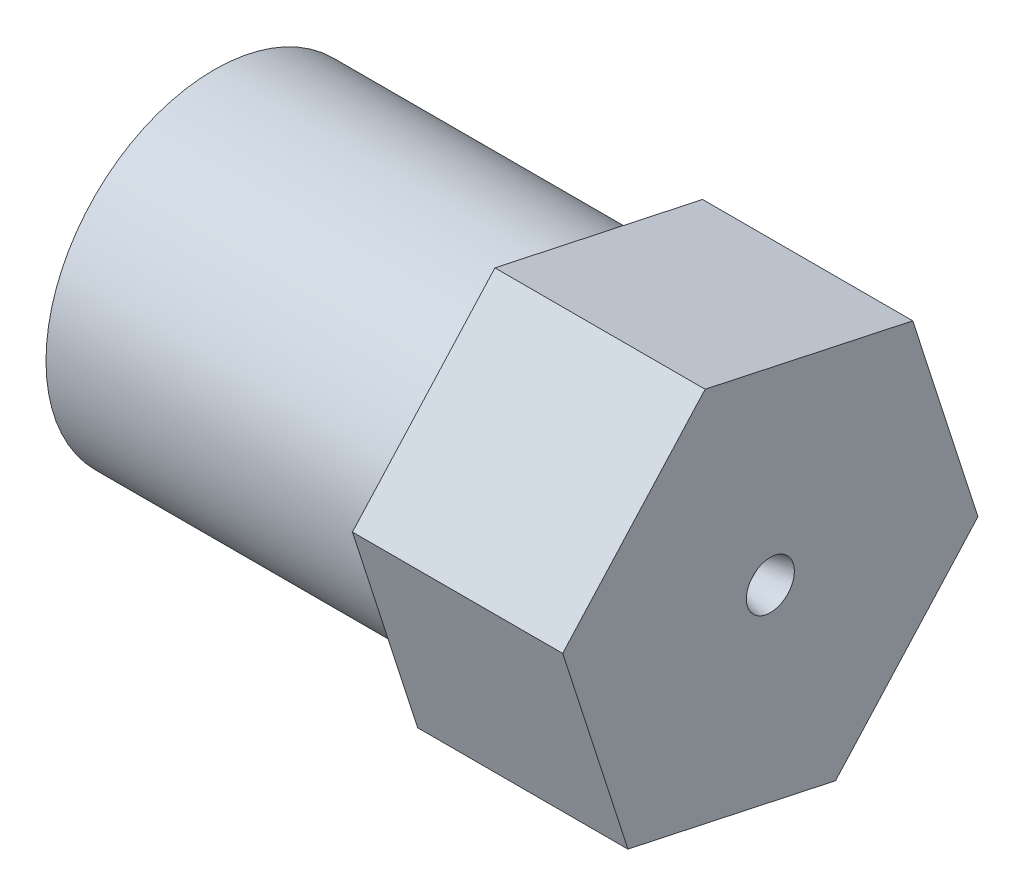
SolidWorks part; units mm, degrees
ref_plane "Front Plane" through (0, 0, 0) normal (0, 0, 1) x (1, 0, 0)
ref_plane "Top Plane" through (0, 0, 0) normal (0, 1, 0) x (1, 0, 0)
ref_plane "Right Plane" through (0, 0, 0) normal (1, 0, 0) x (0, 0, -1)
sketch "Sketch1" plane through (0, 0, 0) normal (0, 0, 1) x (1, 0, 0)
  line L0 (0, 0) -> (1.8499, 0) construction
  line L1 (0.1368, 1.0241) -> (1.8499, 1.6476) construction
  line L2 (-1.0607, 1.4393) -> (-3.1364, 3.5151)
  line L3 (-31.75, 4.445) -> (-31.75, 10.16) construction
  line L4 (-5.3814, 4.445) -> (-31.75, 4.445) construction
  line L5 (-31.75, 10.16) -> (-10.8501, 10.16)
  line L6 (1.8499, 10.16) -> (1.8499, 1.4491)
  line L7 (1.8499, 1.4491) -> (13.1532, 3.0377) construction
  line L8 (-10.8501, 10.16) -> (1.8499, 10.16)
  line L9 (-5.3814, 4.445) -> (-13.462, 4.445)
  line L10 (-19.939, 5.461) -> (-19.939, 6.8199)
  line L11 (-20.066, 6.9469) -> (-24.892, 6.9469)
  line L12 (-24.892, 6.9469) -> (-24.892, 7.8994)
  line L13 (-25.019, 8.0264) -> (-31.115, 8.0264)
  line L14 (-31.75, 10.16) -> (-31.75, 8.6614)
  line L15 (0, 0) -> (-31.75, 0) construction
  line L16 (-13.462, 4.445) -> (-13.462, 4.699)
  line L17 (-13.589, 4.826) -> (-19.304, 4.826)
  arc A0 (-1.0607, 1.4393) -> (0, 1) centre (0, 2.5) ccw
  arc A1 (0, 1) -> (0.1368, 1.0241) centre (0, 1.4) ccw
  arc A2 (-3.1364, 3.5151) -> (-5.3814, 4.445) centre (-5.3814, 1.27) ccw
  arc A3 (-31.115, 8.0264) -> (-31.75, 8.6614) centre (-31.115, 8.6614) cw
  arc A4 (-19.304, 4.826) -> (-19.939, 5.461) centre (-19.304, 5.461) cw
  arc A5 (-13.462, 4.699) -> (-13.589, 4.826) centre (-13.589, 4.699) ccw
  arc A6 (-19.939, 6.8199) -> (-20.066, 6.9469) centre (-20.066, 6.8199) ccw
  arc A7 (-24.892, 7.8994) -> (-25.019, 8.0264) centre (-25.019, 7.8994) ccw
  parabola Q0 (1.8499, 1.4491) -> (0.1368, 1.0241) focus (1.5489, -2.8556) apex (0.1368, 1.0241)
  point P30 (-31.75, 8.0264)
  point P39 (-24.892, 8.0264)
  dimension "D3" = 1.5
  dimension "D4" = 0.4
  dimension "D11" = 3.175
  dimension "D12" = 8
  dimension "D14" = 6.9469
  dimension "D20" = 0.635
  dimension "D21" = 0.127
  dimension "D2" = 1.8499
  dimension "D5" = 1.4491
  dimension "D6" = 20
  dimension "D7" = 45
  dimension "D8" = 8.0264
  dimension "D9" = 31.75
  dimension "D10" = 10.16
  dimension "D13" = 12.7
  dimension "D15" = 4.445
  dimension "D16" = 6.858
  dimension "D17" = 11.811
  dimension "D18" = 18.288
  dimension "D19" = 4.826
  dimension "D22" = 1
revolve "Revolve1" add sketch "Sketch1" angle 360 about L0
sketch "Sketch4" plane through (1.8499, 0, 0) normal (1, 0, 0) x (0, 0, -1)
  line L1 (3.9404, -12.2116) -> (12.5458, -2.6933)
  line L2 (12.5458, -2.6933) -> (8.6054, 9.5183)
  line L3 (8.6054, 9.5183) -> (-3.9404, 12.2116)
  line L4 (-3.9404, 12.2116) -> (-12.5458, 2.6933)
  line L5 (-12.5458, 2.6933) -> (-8.6054, -9.5183)
  line L6 (-8.6054, -9.5183) -> (3.9404, -12.2116)
  circle A0 centre (0, 0) radius 10.16
  circle A1 centre (0, 0) radius 10.16 construction
  circle A2 centre (0, 0) radius 11.1125 construction
  circle M1 centre (0, 0) radius 10.16
  dimension "D1" = 22.225
extrude "Boss-Extrude1" add sketch "Sketch4" against normal blind 12.7 contours L4 L5 M1 | L3 L4 M1 | L2 L3 M1 | L1 L2 M1 | L6 L1 M1 | L5 L6 M1
fillet "Fillet1" radius 0.635 1 edges at (-10.8501, 0, -10.16)
equation "\"D3@Sketch1\"=1.5 * \"D22@Sketch1\""
equation "\"D4@Sketch1\"=.4 * \"D22@Sketch1\""
equation "\"D5@Sketch1\"=\"D22@Sketch1\" * ( \"er\") ^ .5"
equation "\"er\"= 2.1"
